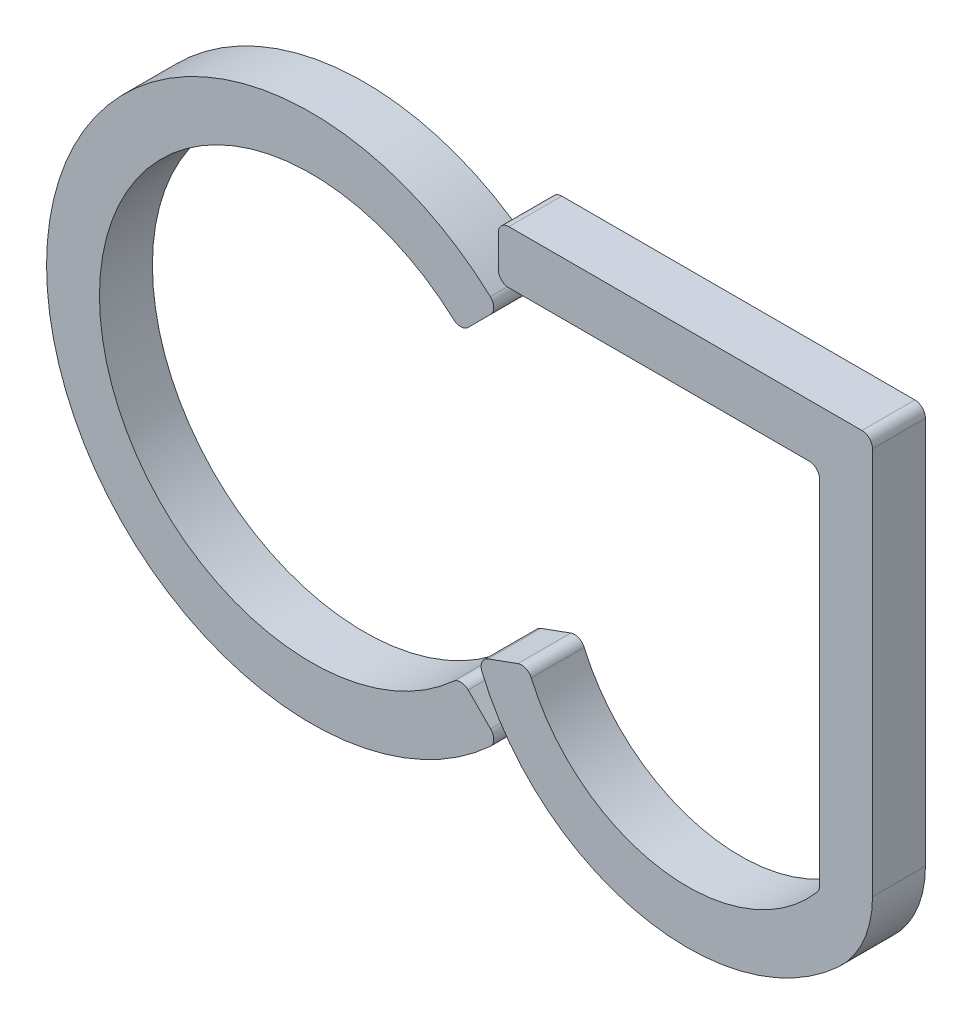
SolidWorks part; units mm, degrees
ref_plane "Alzado" through (0, 0, 0) normal (0, 0, 1) x (1, 0, 0)
ref_plane "Planta" through (0, 0, 0) normal (0, 1, 0) x (1, 0, 0)
ref_plane "Vista lateral" through (0, 0, 0) normal (1, 0, 0) x (0, 0, -1)
sketch "Croquis1" plane through (0, 0, 0) normal (0, 0, 1) x (1, 0, 0)
  line L0 (35.3553, -35.3553) -> (28.2843, -28.2843)
  line L1 (35.3553, 50) -> (106.0709, 50)
  line L2 (35.3553, 40) -> (96.0709, 40)
  line L3 (35.3553, 50) -> (35.3553, 40)
  line L4 (0, 40) -> (106.0709, 40) construction
  line L5 (0, 50) -> (106.0709, 50) construction
  line L6 (28.2843, 28.2843) -> (35.3553, 35.3553)
  line L7 (106.0709, 50) -> (106.0709, -32.4951)
  line L8 (96.0709, 40) -> (96.0709, -29.2187)
  line L9 (40.8932, -19.9825) -> (31.4963, -23.4027)
  arc A0 (35.3553, 35.3553) -> (35.3553, -35.3553) centre (0, 0) ccw
  arc A1 (28.2843, 28.2843) -> (28.2843, -28.2843) centre (0, 0) ccw
  circle A2 centre (0, 0) radius 50 construction
  circle A3 centre (0, 0) radius 40 construction
  arc A4 (40.8932, -19.9825) -> (96.0709, -29.2187) centre (71.0951, -8.9899) ccw
  arc A5 (31.4963, -23.4027) -> (106.0709, -32.4951) centre (71.0951, -8.9899) ccw
  circle A6 centre (71.0951, -8.9899) radius 42.1402 construction
  circle A7 centre (71.0951, -8.9899) radius 32.1402 construction
  point P7 (0, 0)
  point P11 (0, 0)
extrude "Saliente-Extruir1" add sketch "Croquis1" along normal blind 10
fillet "Redondeo1" radius 20 1 edges at (106.0709, -32.4951, 5)
fillet "Redondeo4" radius 2 1 edges at (106.0709, 50, 5)
fillet "Redondeo5" radius 2 6 edges at (96.0709, 40, 5) (96.0709, -29.2187, 5) (40.8932, -19.9825, 5) (31.4963, -23.4027, 5) (35.3553, 40, 5) (35.3553, 50, 5)
fillet "Redondeo6" radius 2 4 edges at (28.2843, 28.2843, 5) (35.3553, 35.3553, 5) (35.3553, -35.3553, 5) (28.2843, -28.2843, 5)
